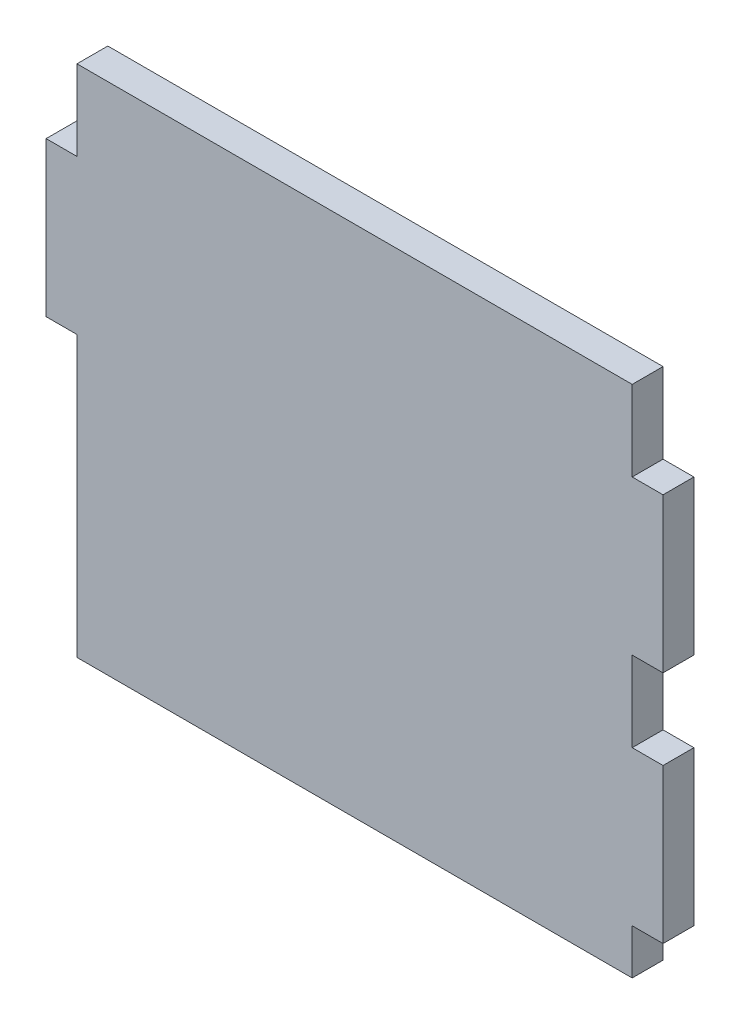
SolidWorks part; units mm, degrees
material "Oak"
ref_plane "Front Plane" through (0, 0, 0) normal (0, 0, 1) x (1, 0, 0)
ref_plane "Top Plane" through (0, 0, 0) normal (0, 1, 0) x (1, 0, 0)
ref_plane "Right Plane" through (0, 0, 0) normal (1, 0, 0) x (0, 0, -1)
sketch "Sketch1" plane through (0, 0, 0) normal (0, 0, 1) x (1, 0, 0)
  line L1 (-40.9935, 16.542) -> (19.0065, 16.542)
  line L2 (-40.9935, 16.542) -> (-40.9935, -33.458)
  line L3 (-40.9935, -33.458) -> (19.0065, -33.458)
  line L4 (19.0065, 16.542) -> (19.0065, -33.458)
  dimension "D1" = 50
  dimension "D2" = 60
extrude "Boss-Extrude1" add sketch "Sketch1" along normal blind 3
sketch "Sketch2" plane through (0, 0, 3) normal (0, 0, 1) x (1, 0, 0)
  line L12 (-40.9935, 16.542) -> (-37.9935, 16.542)
  line L13 (-40.9935, 16.542) -> (-40.9935, 8.742)
  line L14 (-40.9935, 8.742) -> (-37.9935, 8.742)
  line L15 (-37.9935, 16.542) -> (-37.9935, 8.742)
  dimension "D1" = 7.8
  dimension "D2" = 3
extrude "Cut-Extrude1" cut sketch "Sketch2" against normal through all
pattern_linear "LPattern1" count 2 spacing 22.8 along (0, -1, 0) of "Cut-Extrude1"
sketch "Sketch3" plane through (0, 0, 3) normal (0, 0, 1) x (1, 0, 0)
  line L0 (19.0065, 16.542) -> (-37.9935, 16.542) construction
  line L1 (16.0065, 16.542) -> (19.0065, 16.542)
  line L2 (16.0065, 16.542) -> (16.0065, 8.742)
  line L3 (16.0065, 8.742) -> (19.0065, 8.742)
  line L4 (19.0065, 16.542) -> (19.0065, 8.742)
  line L5 (19.0065, -33.458) -> (19.0065, 16.542) construction
  point P8 (17.5065, 16.542)
  dimension "D1" = 7.8
  dimension "D2" = 3
extrude "Cut-Extrude2" cut sketch "Sketch3" against normal through all
pattern_linear "LPattern2" count 4 spacing 22.8 along (0, -1, 0) of "Cut-Extrude2"
sketch "Sketch6" plane through (0, 0, 3) normal (0, 0, 1) x (1, 0, 0)
  line L0 (-40.9935, -33.458) -> (16.0065, -33.458) construction
  line L1 (-40.9935, -14.058) -> (-37.9935, -14.058)
  line L2 (-40.9935, -14.058) -> (-40.9935, -33.458)
  line L3 (-40.9935, -33.458) -> (-37.9935, -33.458)
  line L4 (-37.9935, -14.058) -> (-37.9935, -33.458)
  dimension "D1" = 3
extrude "Cut-Extrude3" cut sketch "Sketch6" against normal blind 10
